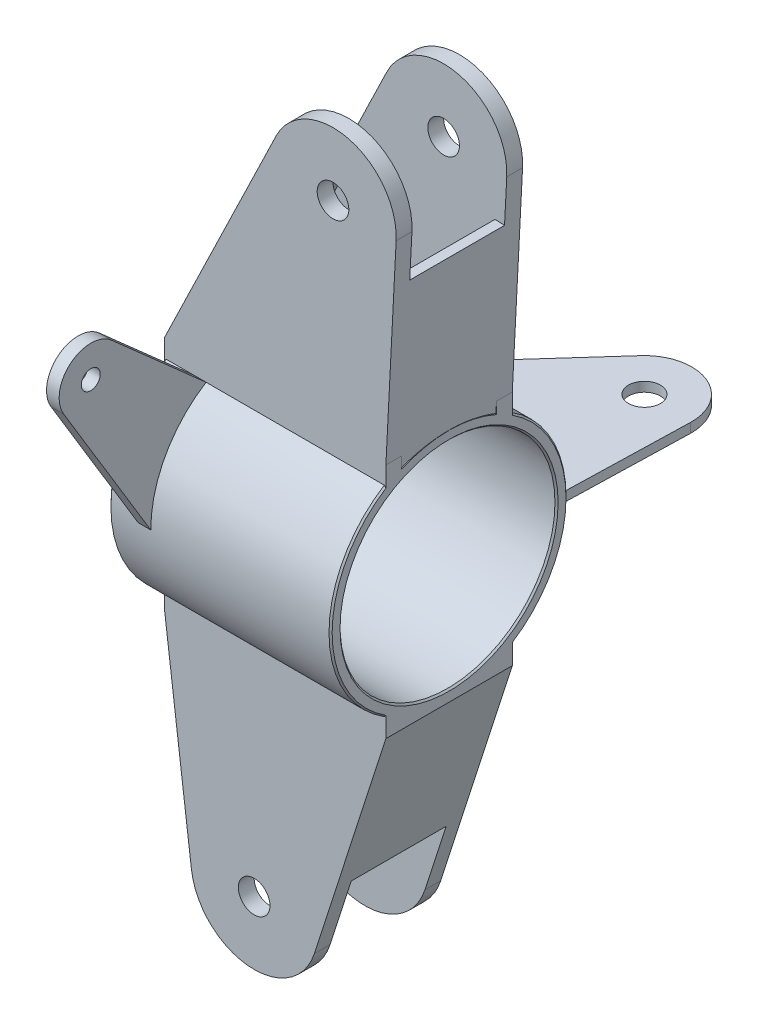
SolidWorks part; units mm, degrees
ref_plane "Front Plane" through (0, 0, 0) normal (0, 0, 1) x (1, 0, 0)
ref_plane "Top Plane" through (0, 0, 0) normal (0, 1, 0) x (1, 0, 0)
ref_plane "Right Plane" through (0, 0, 0) normal (1, 0, 0) x (0, 0, -1)
sketch "Sketch1" plane through (0, 0, 0) normal (1, 0, 0) x (0, 0, -1)
  circle A0 centre (0, 0) radius 34.007
  circle A1 centre (0, 0) radius 37.5
  dimension "D1" = 68.014
  dimension "D2" = 75
extrude "Boss-Extrude1" add sketch "Sketch1" along normal mid plane 70
sketch "Sketch4" plane through (0, 0, 0) normal (0, 0, 1) x (1, 0, 0)
  line L0 (-35, 0) -> (5.8, 0) construction
  line L1 (-35, 37.5) -> (-35, -37.5) construction
  line L2 (5.8, 101.6) -> (5.8, -101.6) construction
  line L3 (18.2749, 101.6) -> (-6.6749, -101.6) construction
  line L4 (0.2757, 110.3193) -> (-35, 37.5)
  line L5 (35, 37.5) -> (38.2484, 100.5713)
  line L6 (-35, -37.5) -> (-26.5147, -104.1267)
  line L7 (35, -37.5) -> (12.3606, -107.7358)
  line L8 (-35, -37.5) -> (35, -37.5) construction
  line L9 (-35, -37.5) -> (35, -37.5)
  line L10 (35, 37.5) -> (-35, 37.5) construction
  line L11 (35, 37.5) -> (-35, 37.5)
  circle A0 centre (18.2749, 101.6) radius 5.007
  circle A1 centre (-6.6749, -101.6) radius 5.007
  arc A2 (38.2484, 100.5713) -> (0.2757, 110.3193) centre (18.2749, 101.6) ccw
  arc A3 (-26.5147, -104.1267) -> (12.3606, -107.7358) centre (-6.6749, -101.6) ccw
  point P7 (5.8, 0)
  point P11 (5.8, 0)
  dimension "D4" = 10.014
  dimension "D5" = 203.2
  dimension "D2" = 20
  dimension "D1" = 40.8
  dimension "D3" = 7
extrude "Boss-Extrude2" add sketch "Sketch4" along normal blind 5 from offset 15 separate body
sketch "Sketch5" plane through (0, 0, 0) normal (0, 0, 1) x (1, 0, 0)
  line L0 (35, -37.5) -> (-35, -37.5) construction
  line L1 (-35, -37.5) -> (-26.5147, -104.1267) construction
  line L2 (12.3606, -107.7358) -> (35, -37.5) construction
  line L3 (35, 37.5) -> (38.2484, 100.5713) construction
  line L4 (-35, 37.5) -> (35, 37.5) construction
  line L5 (0.2757, 110.3193) -> (-35, 37.5) construction
  line L6 (35, -37.5) -> (-35, -37.5)
  line L7 (-35, -37.5) -> (-26.5147, -104.1267)
  line L8 (12.3606, -107.7358) -> (35, -37.5)
  line L9 (35, 37.5) -> (38.2484, 100.5713)
  line L10 (-35, 37.5) -> (35, 37.5)
  line L11 (0.2757, 110.3193) -> (-35, 37.5)
  arc A0 (-26.5147, -104.1267) -> (12.3606, -107.7358) centre (-6.6749, -101.6) ccw construction
  circle A1 centre (-6.6749, -101.6) radius 5.007 construction
  circle A2 centre (18.2749, 101.6) radius 5.007 construction
  arc A3 (38.2484, 100.5713) -> (0.2757, 110.3193) centre (18.2749, 101.6) ccw construction
  arc A4 (-26.5147, -104.1267) -> (12.3606, -107.7358) centre (-6.6749, -101.6) ccw
  circle A5 centre (-6.6749, -101.6) radius 5.007
  circle A6 centre (18.2749, 101.6) radius 5.007
  arc A7 (38.2484, 100.5713) -> (0.2757, 110.3193) centre (18.2749, 101.6) ccw
extrude "Boss-Extrude3" add sketch "Sketch5" against normal blind 5 from offset 15 separate body offset against normal yes
sketch "Sketch6" plane through (35, 0, 0) normal (1, 0, 0) x (0, 0, -1)
  line L0 (20, -37.5) -> (15, -37.5) construction
  line L1 (-20, -37.5) -> (-15, -37.5) construction
  line L2 (20, 37.5) -> (15, 37.5) construction
  line L3 (-20, 37.5) -> (-15, 37.5) construction
  line L4 (20, -37.5) -> (15, -37.5)
  line L5 (-20, -37.5) -> (-15, -37.5)
  line L6 (20, 37.5) -> (15, 37.5)
  line L7 (-20, 37.5) -> (-15, 37.5)
  line L8 (-20, 37.5) -> (-20, 31.7214)
  line L9 (-15, 37.5) -> (-15, 34.3693)
  line L10 (15, 37.5) -> (15, 34.3693)
  line L11 (20, 37.5) -> (20, 31.7214)
  line L12 (-20, -37.5) -> (-20, -31.7214)
  line L13 (-15, -37.5) -> (-15, -34.3693)
  line L14 (15, -37.5) -> (15, -34.3693)
  line L15 (20, -37.5) -> (20, -31.7214)
  circle A0 centre (0, 0) radius 37.5 construction
  arc A1 (-20, -31.7214) -> (-15, -34.3693) centre (0, 0) ccw
  arc A2 (-15, 34.3693) -> (-20, 31.7214) centre (0, 0) ccw
  arc A3 (20, 31.7214) -> (15, 34.3693) centre (0, 0) ccw
  arc A4 (15, -34.3693) -> (20, -31.7214) centre (0, 0) ccw
extrude "Boss-Extrude4" add sketch "Sketch6" against normal up to surface (70 mm away) up to face at (-35, 0, -37.5)
chamfer "Chamfer1" distance 0.5 angle 45 5 edges at (35, 0, -34.007) (35, 0, -37.5) (35, 37.5, 0) (35, 0, 37.5) (35, -37.5, 0)
chamfer "Chamfer2" distance 0.5 angle 45 5 edges at (-35, 0, -37.5) (-35, -37.5, 0) (-35, 0, 37.5) (-35, 37.5, 0) (-35, 0, -34.007)
sketch "Sketch12" plane through (32.9811, -1.6987, 0) normal (0.9987, -0.0514, 0) x (0, 0, -1)
  line L0 (-15, 39.2506) -> (-15, 102.4055) construction
  line L1 (-15, 35.5786) -> (-15, 39.2506) construction
  line L2 (15, 39.2506) -> (15, 35.5786) construction
  line L3 (15, 39.2506) -> (15, 102.4055) construction
  line L4 (-15, 39.2506) -> (-15, 88.7513)
  line L5 (-15, 35.5786) -> (-15, 39.2506)
  line L6 (15, 39.2506) -> (15, 35.5786)
  line L7 (15, 39.2506) -> (15, 88.7513)
  line L8 (-15, 88.7513) -> (15, 88.7513)
  ellipse E0 centre (0, 1.8003) end of major axis (37, 1.8003) minor radius 36.951 (15, 35.5786) -> (-15, 35.5786) ccw construction
  ellipse E1 centre (0, 1.8003) end of major axis (37, 1.8003) minor radius 36.951 (15, 35.5786) -> (-15, 35.5786) ccw
  dimension "D1" = 50
extrude "Boss-Extrude8" add sketch "Sketch12" against normal blind 3
sketch "Sketch13" plane through (-43.0609, 20.8599, 0) normal (-0.9, 0.436, 0) x (0, 0, 1)
  line L0 (15, 99.4035) -> (15, 18.4898) construction
  line L1 (-15, 99.4035) -> (-15, 18.4898) construction
  line L2 (15, 73.4898) -> (15, 18.4898)
  line L3 (-15, 73.4898) -> (-15, 18.4898)
  line L4 (-15, 18.4898) -> (15, 18.4898)
  line L5 (-15, 73.4898) -> (15, 73.4898)
  dimension "D1" = 55
extrude "Boss-Extrude9" add sketch "Sketch13" against normal blind 3
sketch "Sketch14" plane through (-35, 0, 0) normal (-1, 0, 0) x (0, 0, 1)
  line L0 (15, 37.5) -> (15, 33.8231) construction
  line L1 (-15, 33.8231) -> (-15, 37.5) construction
  line L2 (-15, 37.5) -> (15, 37.5) construction
  line L3 (15, 37.5) -> (15, 33.8231)
  line L4 (-15, 33.8231) -> (-15, 37.5)
  line L5 (-15, 37.5) -> (15, 37.5)
  arc A0 (15, 33.8231) -> (-15, 33.8231) centre (0, 0) ccw construction
  arc A1 (15, 33.8231) -> (-15, 33.8231) centre (0, 0) ccw
extrude "Boss-Extrude10" add sketch "Sketch14" against normal blind 3
sketch "Sketch15" plane through (-39.141, -4.9849, 0) normal (-0.992, -0.1263, 0) x (0, 0, 1)
  line L0 (15, -32.7778) -> (15, -99.9427) construction
  line L1 (-15, -32.7778) -> (-15, -99.9427) construction
  line L2 (15, -32.7778) -> (15, -82.7778)
  line L3 (-15, -32.7778) -> (-15, -82.7778)
  line L4 (-15, -32.7778) -> (15, -32.7778)
  line L6 (-15, -82.7778) -> (15, -82.7778)
  dimension "D1" = 50
extrude "Boss-Extrude11" add sketch "Sketch15" against normal blind 3
sketch "Sketch16" plane through (-35, 0, 0) normal (-1, 0, 0) x (0, 0, 1)
  line L0 (15, -37.5) -> (-15, -37.5) construction
  line L1 (15, -33.8231) -> (15, -37.5) construction
  line L2 (-15, -37.5) -> (-15, -33.8231) construction
  line L3 (15, -37.5) -> (-15, -37.5)
  line L4 (15, -33.8231) -> (15, -37.5)
  line L5 (-15, -37.5) -> (-15, -33.8231)
  arc A0 (-15, -33.8231) -> (15, -33.8231) centre (0, 0) ccw construction
  arc A1 (-15, -33.8231) -> (15, -33.8231) centre (0, 0) ccw
extrude "Boss-Extrude12" add sketch "Sketch16" against normal blind 3
sketch "Sketch17" plane through (42.6556, -13.7493, 0) normal (0.9518, -0.3068, 0) x (0, 0, -1)
  line L0 (-15, -98.7484) -> (-15, -24.954) construction
  line L1 (15, -98.7484) -> (15, -24.954) construction
  line L2 (-15, -76.954) -> (-15, -24.954)
  line L3 (15, -76.954) -> (15, -24.954)
  line L4 (-15, -24.954) -> (15, -24.954)
  line L6 (-15, -76.954) -> (15, -76.954)
  dimension "D1" = 52
extrude "Boss-Extrude13" add sketch "Sketch17" against normal blind 3
sketch "Sketch19" plane through (35, 0, 0) normal (1, 0, 0) x (0, 0, -1)
  line L1 (15, -37.5) -> (-15, -37.5) construction
  line L2 (-15, -37.5) -> (-15, -33.8231) construction
  line L3 (15, -33.8231) -> (15, -37.5) construction
  line L4 (-15, -37.5) -> (-15, -33.8231)
  line L5 (15, -33.8231) -> (15, -37.5)
  line L6 (15, -37.5) -> (-15, -37.5)
  arc A0 (-15, -33.8231) -> (15, -33.8231) centre (0, 0) ccw construction
  arc A1 (-15, -33.8231) -> (15, -33.8231) centre (0, 0) ccw
extrude "Boss-Extrude14" add sketch "Sketch19" against normal blind 3
sketch "Sketch21" plane through (0, 0, 0) normal (0, 1, 0) x (1, 0, 0)
  line L0 (34.5, 37.5) -> (-34.5, 37.5) construction
  line L1 (34.5, 37.5) -> (-34.5, 37.5)
  line L2 (0, 0) -> (0, 109.7901) construction
  line L3 (0, 0) -> (20.5384, 76.2773) construction
  line L4 (34.5, 37.5) -> (35.5329, 75.8737)
  line L5 (-34.5, 37.5) -> (9.3842, 86.3065)
  circle A0 centre (20.5384, 76.2773) radius 5.05
  arc A1 (35.5329, 75.8737) -> (9.3842, 86.3065) centre (20.5384, 76.2773) ccw
  dimension "D3" = 10.1
  dimension "D4" = 30
  dimension "D1" = 15.07
  dimension "D2" = 78.994
extrude "Boss-Extrude15" add sketch "Sketch21" along normal mid plane 3 separate body
ref_plane "Plane1" through (-25.9, 0, 0) normal (1, 0, 0) x (0, 0, -1)
sketch "Sketch22" plane through (-25.9, 0, 0) normal (1, 0, 0) x (0, 0, -1)
  line L0 (-20, 31.7214) -> (-49.8466, 58.1521)
  line L1 (0, 0) -> (-37.5, 0) construction
  line L2 (-37.5, 0) -> (-65.0313, 45.4877)
  circle A0 centre (-56.4762, 50.6656) radius 3
  arc A1 (-49.8466, 58.1521) -> (-65.0313, 45.4877) centre (-56.4762, 50.6656) ccw
  arc A2 (-20, 31.7214) -> (-20, -31.7214) centre (0, 0) ccw construction
  arc A3 (-20, 31.7214) -> (-37.5, 0) centre (0, 0) ccw
  dimension "D1" = 6
  dimension "D2" = 20
extrude "Boss-Extrude16" add sketch "Sketch22" along normal blind 4
